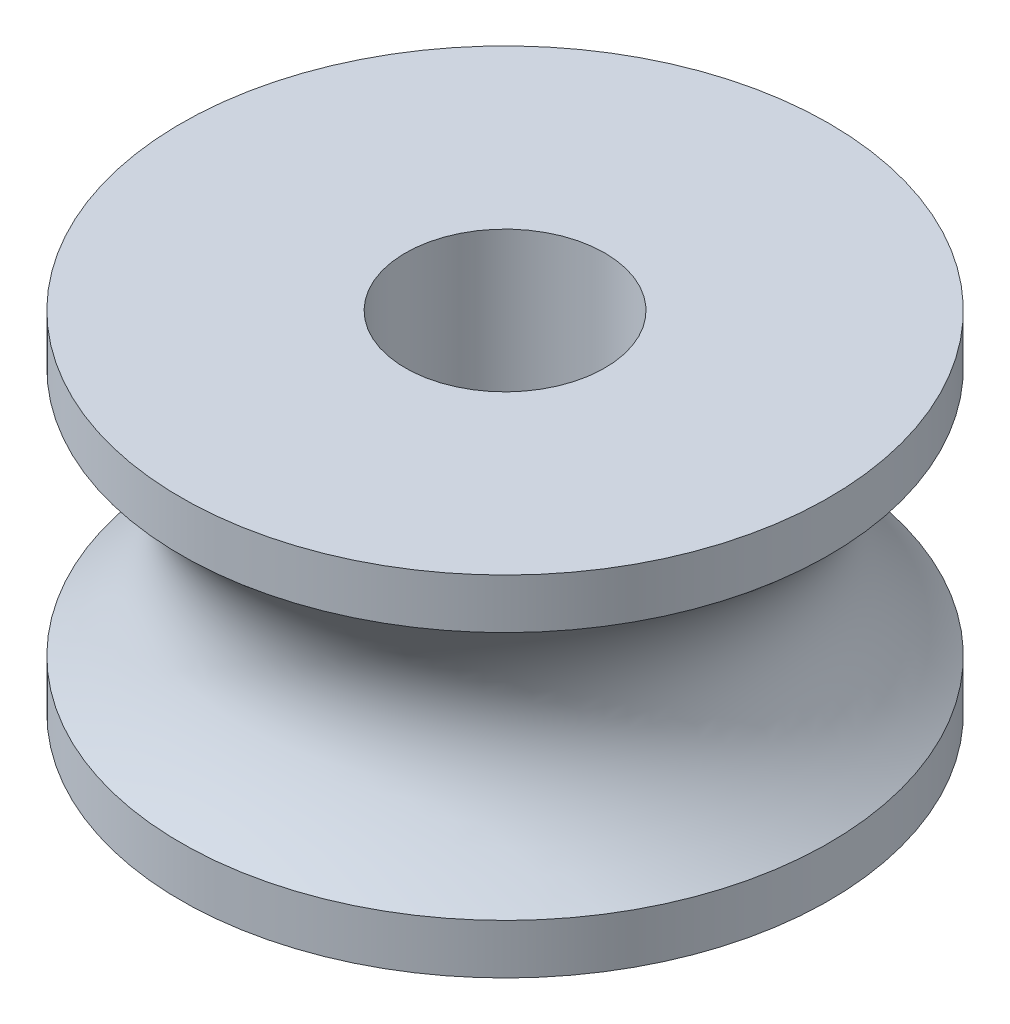
SolidWorks part; units mm, degrees
ref_plane "正面" through (0, 0, 0) normal (0, 0, 1) x (1, 0, 0)
ref_plane "平面" through (0, 0, 0) normal (0, 1, 0) x (1, 0, 0)
ref_plane "右側面" through (0, 0, 0) normal (1, 0, 0) x (0, 0, -1)
sketch "ｽｹｯﾁ1" plane through (0, 0, 0) normal (0, 0, 1) x (1, 0, 0)
  line L0 (0, 0) -> (0, 7) construction
  line L1 (0, 7) -> (6.5, 7)
  line L2 (6.5, 7) -> (6.5, 6)
  line L3 (0, 0) -> (6.5, 0)
  line L4 (6.5, 0) -> (6.5, 1)
  line L5 (0, 3.5) -> (5, 3.5) construction
  line L6 (0, 0) -> (0, 7)
  spline S0 degree 2 poles (6.5, 6) (3.5, 3.5) (6.5, 1) knots 0 0 0 1 1 1
  dimension "D1" = 7
  dimension "D2" = 13
  dimension "D3" = 1
  dimension "D4" = 10
revolve "回転1" add sketch "ｽｹｯﾁ1" angle 360 about L6
sketch "ｽｹｯﾁ2" plane through (0, 0, 0) normal (0, -1, 0) x (1, 0, 0)
  circle A0 centre (0, 0) radius 2
  dimension "D1" = 4
extrude "ｶｯﾄ - 押し出し1" cut sketch "ｽｹｯﾁ2" against normal blind 10
ref_plane "平面1" through (0, 3.5, 0) normal (0, -1, 0) x (-1, 0, 0)
